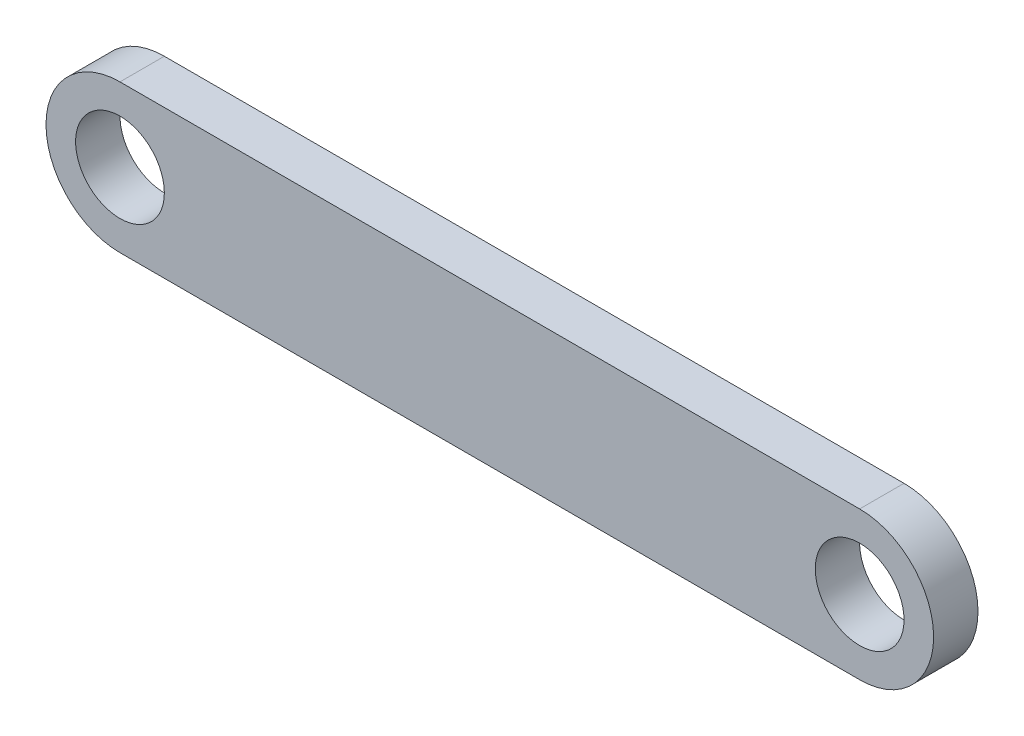
SolidWorks part; units mm, degrees
ref_plane "正面" through (0, 0, 0) normal (0, 0, 1) x (1, 0, 0)
ref_plane "平面" through (0, 0, 0) normal (0, 1, 0) x (1, 0, 0)
ref_plane "右側面" through (0, 0, 0) normal (1, 0, 0) x (0, 0, -1)
sketch "ｽｹｯﾁ1" plane through (0, 0, 0) normal (0, 0, 1) x (1, 0, 0)
  line L0 (-25, 0) -> (25, 0) construction
  line L1 (-25, 5) -> (25, 5)
  line L2 (-25, -5) -> (25, -5)
  arc A0 (-25, 5) -> (-25, -5) centre (-25, 0) ccw
  arc A1 (25, -5) -> (25, 5) centre (25, 0) ccw
  circle A2 centre (-25, 0) radius 3
  circle A3 centre (25, 0) radius 3
  point P2 (0, 0)
  dimension "D1" = 6
  dimension "D2" = 5
  dimension "D3" = 50
extrude "ﾎﾞｽ - 押し出し1" add sketch "ｽｹｯﾁ1" along normal blind 3
